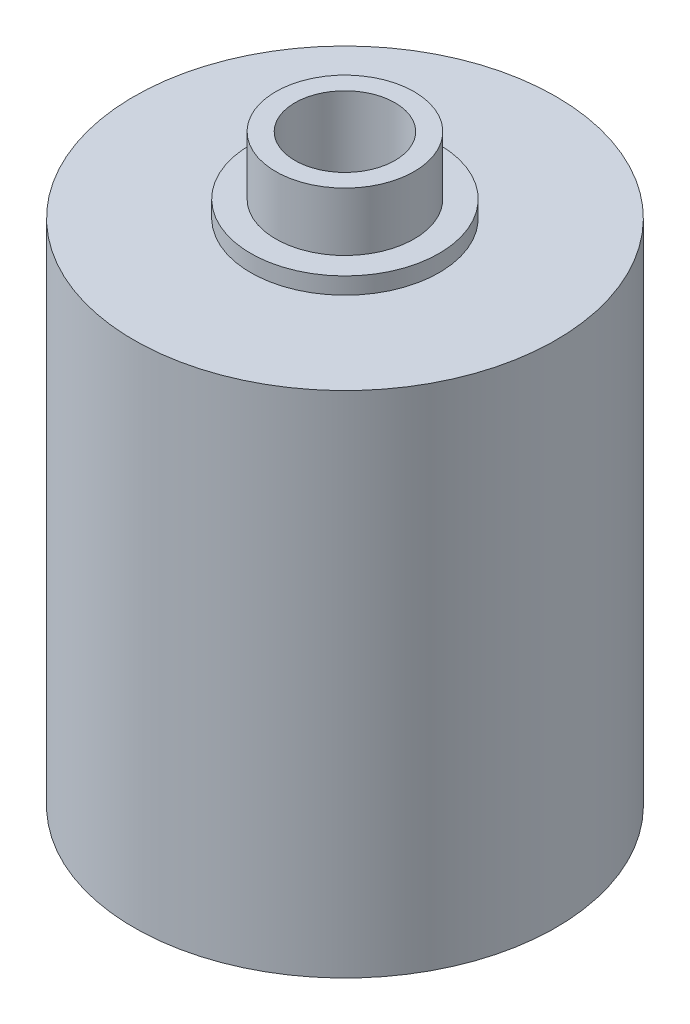
SolidWorks part; units mm, degrees
ref_plane "Спереди" through (0, 0, 0) normal (0, 0, 1) x (1, 0, 0)
ref_plane "Сверху" through (0, 0, 0) normal (0, 1, 0) x (1, 0, 0)
ref_plane "Справа" through (0, 0, 0) normal (1, 0, 0) x (0, 0, -1)
sketch "Эскиз1" plane through (0, 0, 0) normal (0, 0, 1) x (1, 0, 0)
  line L0 (0, 20) -> (3, 20)
  line L1 (3, 20) -> (3, 35)
  line L2 (3, 35) -> (4.15, 35)
  line L3 (4.15, 35) -> (4.15, 31.5)
  line L4 (4.15, 31.5) -> (5.65, 31.5)
  line L5 (12.65, 30.5) -> (12.65, 0)
  line L6 (12.65, 0) -> (0, 0)
  line L7 (0, 0) -> (0, 20)
  line L8 (0, 0) -> (0, 31.0859) construction
  line L9 (5.65, 31.5) -> (5.65, 30.5)
  line L10 (5.65, 30.5) -> (12.65, 30.5)
  point P6 (3, 3.2649)
  point P13 (0, 0)
  dimension "D1" = 3
  dimension "D2" = 4.15
  dimension "D3" = 3.5
  dimension "D4" = 1.5
  dimension "D5" = 1
  dimension "D6" = 12.65
  dimension "D7" = 15
  dimension "D8" = 20
revolve "Повернуть1" add sketch "Эскиз1" angle 360 about L8
sketch "Эскиз2" plane through (0, 0, 0) normal (0, -1, 0) x (1, 0, 0)
  line L1 (-7.6, 7.6) -> (7.6, 7.6)
  line L2 (-7.6, 7.6) -> (-7.6, -7.6)
  line L3 (-7.6, -7.6) -> (7.6, -7.6)
  line L4 (7.6, 7.6) -> (7.6, -7.6)
  line L5 (-7.6, 7.6) -> (7.6, -7.6) construction
  line L6 (-7.6, -7.6) -> (7.6, 7.6) construction
  point P0 (0, 0)
  dimension "D1" = 15.2
  dimension "D2" = 15.2
extrude "Вырез-Вытянуть1" cut sketch "Эскиз2" against normal blind 25
